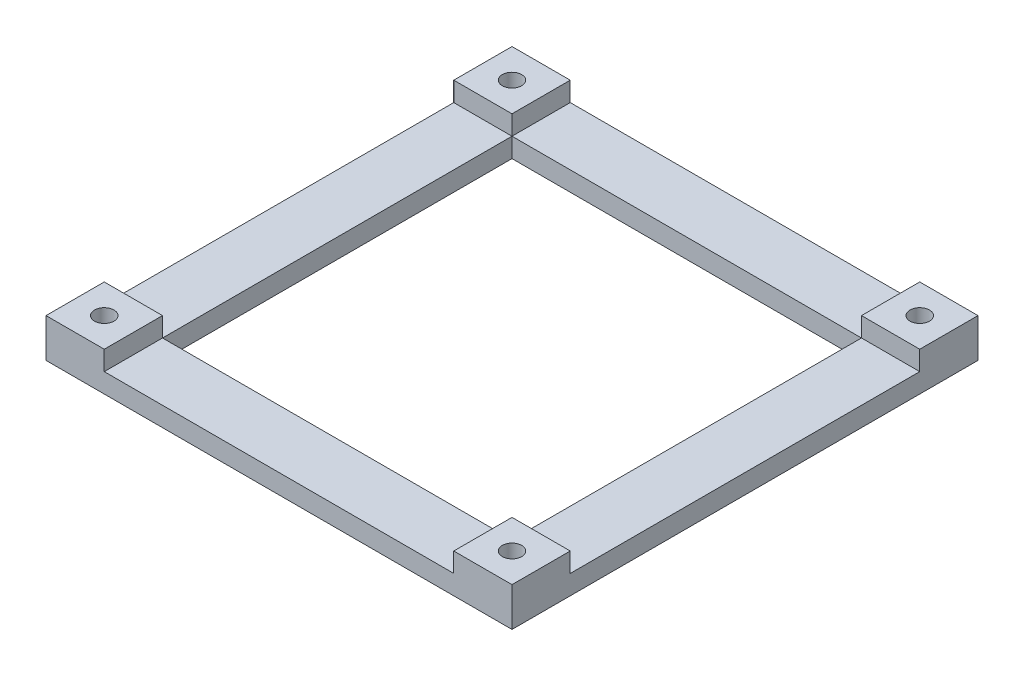
SolidWorks part; units mm, degrees
ref_plane "Front Plane" through (0, 0, 0) normal (0, 0, 1) x (1, 0, 0)
ref_plane "Top Plane" through (0, 0, 0) normal (0, 1, 0) x (1, 0, 0)
ref_plane "Right Plane" through (0, 0, 0) normal (1, 0, 0) x (0, 0, -1)
sketch "Sketch2" plane through (0, 0, 0) normal (0, 1, 0) x (1, 0, 0)
  line L0 (-45, 45) -> (45, 45)
  line L1 (-60, -60) -> (60, -60)
  line L2 (-60, -60) -> (-60, 60)
  line L3 (-60, 60) -> (60, 60)
  line L4 (60, -60) -> (60, 60)
  line L5 (-60, -60) -> (60, 60) construction
  line L6 (-60, 60) -> (60, -60) construction
  line L7 (45, -45) -> (45, 45)
  line L8 (-45, -45) -> (45, -45)
  line L9 (-45, -45) -> (-45, 45)
  point P0 (0, 0)
  dimension "D1" = 120
  dimension "D2" = 120
  dimension "D3" = 15
extrude "Boss-Extrude1" add sketch "Sketch2" along normal blind 5
sketch "Sketch3" plane through (0, 5, 0) normal (0, 1, 0) x (1, 0, 0)
  line L0 (45, 45) -> (45, 60)
  line L1 (-45, 45) -> (-60, 45)
  line L2 (-45, 45) -> (-45, 60)
  line L3 (-45, 60) -> (-60, 60)
  line L4 (-60, 45) -> (-60, 60)
  line L5 (45, 60) -> (60, 60)
  line L6 (45, 45) -> (60, 45)
  line L7 (60, 45) -> (60, 60)
  line L8 (45, -45) -> (60, -45)
  line L9 (60, -45) -> (60, -60)
  line L10 (45, -45) -> (45, -60)
  line L11 (45, -60) -> (60, -60)
  line L12 (-45, -45) -> (-45, -60)
  line L13 (-45, -60) -> (-60, -60)
  line L14 (-45, -45) -> (-60, -45)
  line L15 (-60, -45) -> (-60, -60)
  line L16 (-60, 60) -> (60, -60) construction
  line L17 (60, 60) -> (-60, -60) construction
  point P21 (0, 0)
  dimension "D2" = 90
  dimension "D1" = 4
extrude "Boss-Extrude2" add sketch "Sketch3" along normal blind 5
sketch "Sketch4" plane through (0, 10, 0) normal (0, 1, 0) x (1, 0, 0)
  line L0 (-60, -45) -> (-45, -60) construction
  line L1 (-45, -45) -> (-60, -60) construction
  line L2 (-60, -60) -> (60, 60) construction
  line L3 (-60, 60) -> (60, -60) construction
  circle A0 centre (-52.5, -52.5) radius 2.5
  circle A1 centre (-52.5, 52.5) radius 2.5
  circle A2 centre (52.5, 52.5) radius 2.5
  circle A3 centre (52.5, -52.5) radius 2.5
  point P19 (0, 0)
  dimension "D1" = 5
  dimension "D2" = 4
extrude "Cut-Extrude1" cut sketch "Sketch4" against normal through all
